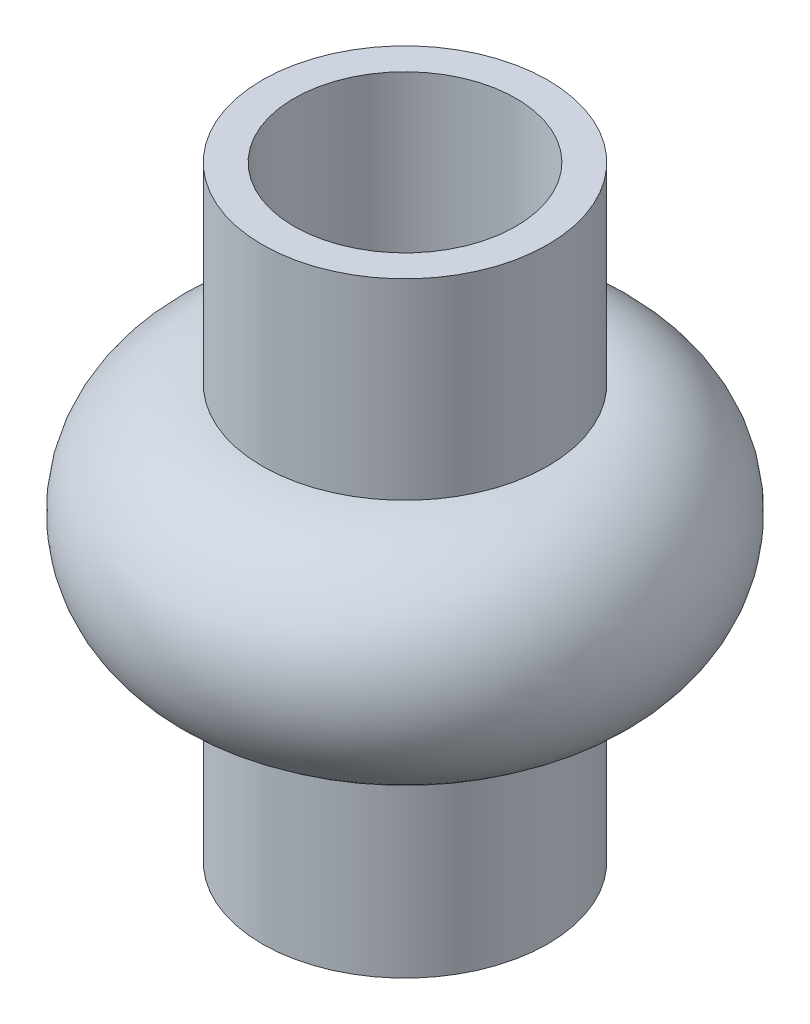
SolidWorks part; units mm, degrees
material "NEOPRENE"
ref_plane "Front Plane" through (0, 0, 0) normal (0, 0, 1) x (1, 0, 0)
ref_plane "Top Plane" through (0, 0, 0) normal (0, 1, 0) x (1, 0, 0)
ref_plane "Right Plane" through (0, 0, 0) normal (1, 0, 0) x (0, 0, -1)
sketch "Sketch1" plane through (0, 0, 0) normal (0, 0, 1) x (1, 0, 0)
  line L0 (-16, 0) -> (0, 0) construction
  line L1 (-9, -19.1) -> (-7, -19.1)
  line L2 (-9, -19.1) -> (-9, -7)
  line L3 (-9, -7) -> (-7, -7)
  line L4 (-7, -19.1) -> (-7, -7)
  line L5 (-9, -19.1) -> (-7, -7) construction
  line L6 (-9, -7) -> (-7, -19.1) construction
  line L7 (-9, 19.1) -> (-7, 19.1)
  line L8 (-9, 19.1) -> (-9, 7)
  line L9 (-9, 7) -> (-7, 7)
  line L10 (-7, 19.1) -> (-7, 7)
  line L11 (-9, 19.1) -> (-7, 7) construction
  line L12 (-9, 7) -> (-7, 19.1) construction
  line L13 (0, 18.4627) -> (0, -18.3841) construction
  line L14 (-11.25, 5) -> (-11.25, -5) construction
  arc A0 (-9, -7) -> (-9, 7) centre (-9, 0) cw
  spline S0 degree 3 poles (-7, 7) (-7, 5.3289) (-12.6998, 5.9907) (-14.7132, -0.0226) (-12.6998, -5.9083) (-7, -5.4646) (-7, -7) knots 0 0 0 0 0.225746 0.5 0.774254 1 1 1 1
  point P0 (-8, -13.05)
  point P5 (-8, 13.05)
  point P21 (-8.0237, 5.1126)
  point P22 (-11.25, 0)
  point P23 (-10.5973, 5)
  point P24 (-12.3905, 5)
  point P25 (-10.7396, 5)
  point P26 (-14, 0)
  point P27 (-7.8907, -5)
  point P28 (-14, 0)
  point P29 (-11.2076, -5)
  point P30 (-11.2259, 5)
  dimension "D1" = 7
  dimension "D2" = 2
  dimension "D3" = 38.2
  dimension "D4" = 14
  dimension "D5" = 2
  dimension "D6" = 2
  dimension "D7" = 4.75
revolve "Revolve1" add sketch "Sketch1" angle 360 about L13
